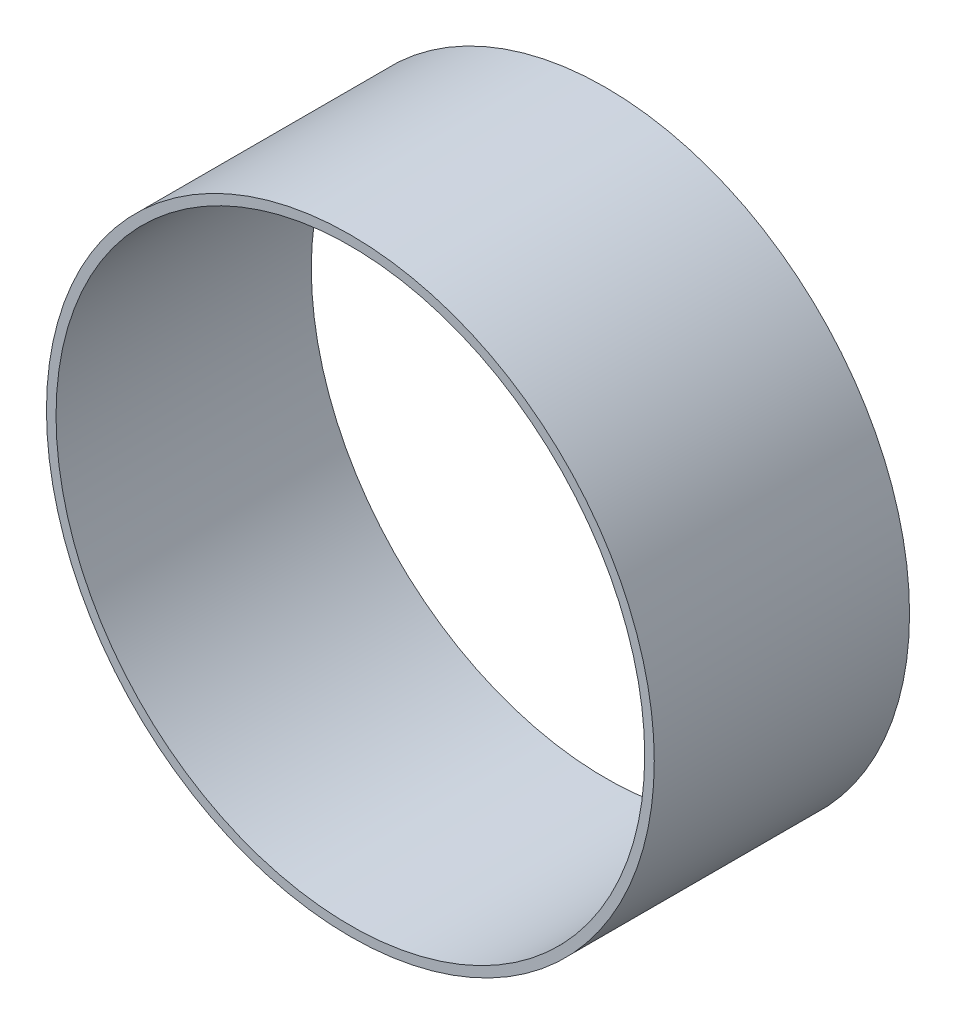
SolidWorks part; units mm, degrees
ref_plane "Спереди" through (0, 0, 0) normal (0, 0, 1) x (1, 0, 0)
ref_plane "Сверху" through (0, 0, 0) normal (0, 1, 0) x (1, 0, 0)
ref_plane "Справа" through (0, 0, 0) normal (1, 0, 0) x (0, 0, -1)
sketch "Эскиз1" plane through (0, 0, 0) normal (0, 0, 1) x (1, 0, 0)
  circle A0 centre (0, 0) radius 95.2462
  circle A1 centre (0, 0) radius 92.2462
extrude "Rotor_shell" add sketch "Эскиз1" along normal blind 80 from offset 40
